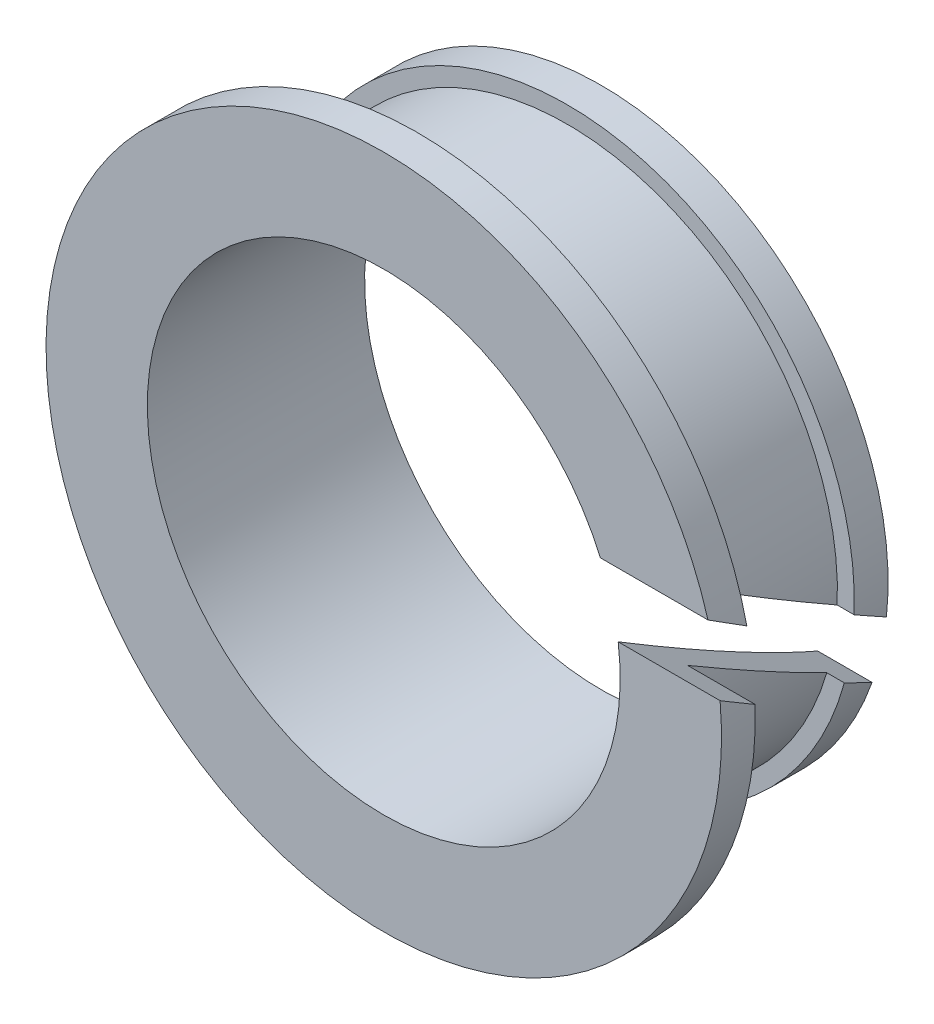
SolidWorks part; units mm, degrees
ref_plane "Front Plane" through (0, 0, 0) normal (0, 0, 1) x (1, 0, 0)
ref_plane "Top Plane" through (0, 0, 0) normal (0, 1, 0) x (1, 0, 0)
ref_plane "Right Plane" through (0, 0, 0) normal (1, 0, 0) x (0, 0, -1)
sketch "Sketch1" plane through (0, 0, 0) normal (1, 0, 0) x (0, 0, -1)
  line L0 (-22.5136, 0) -> (24.6784, 0) construction
  line L1 (-2.5527, 5.5562) -> (2.5527, 5.5562)
  line L2 (2.5527, 5.5562) -> (2.5527, 6.7469)
  line L3 (2.5527, 6.7469) -> (1.759, 6.7469)
  line L4 (1.759, 6.7469) -> (1.759, 6.35)
  line L5 (1.759, 6.35) -> (-1.759, 6.35)
  line L6 (-1.759, 6.35) -> (-1.759, 7.9375)
  line L7 (-1.759, 7.9375) -> (-2.5527, 7.9375)
  line L8 (-2.5527, 7.9375) -> (-2.5527, 5.5562)
  point P10 (0, 5.5562)
  dimension "D1" = 11.1125
  dimension "D2" = 15.875
  dimension "D3" = 5.1054
  dimension "D4" = 12.7
  dimension "D5" = 13.4937
  dimension "D6" = 0.7937
revolve "Revolve1" add sketch "Sketch1" angle 360 about L0
sketch "Sketch2" plane through (0, 0, 0) normal (1, 0, 0) x (0, 0, -1)
  line L0 (-2.5527, 0.7238) -> (-2.5527, 2.2238)
  line L1 (-2.5527, 7.9375) -> (-2.5527, -7.9375) construction
  line L2 (-2.5527, 2.2238) -> (2.5527, -0.7238)
  line L3 (2.5527, -6.7469) -> (2.5527, 6.7469) construction
  line L4 (2.5527, -0.7238) -> (2.5527, -2.2238)
  line L5 (2.5527, -2.2238) -> (-2.5527, 0.7238)
  line L6 (0, 0.75) -> (0, -0.75) construction
  dimension "D1" = 1.5
  dimension "D2" = 60
extrude "Cut-Extrude1" cut sketch "Sketch2" along normal through all
